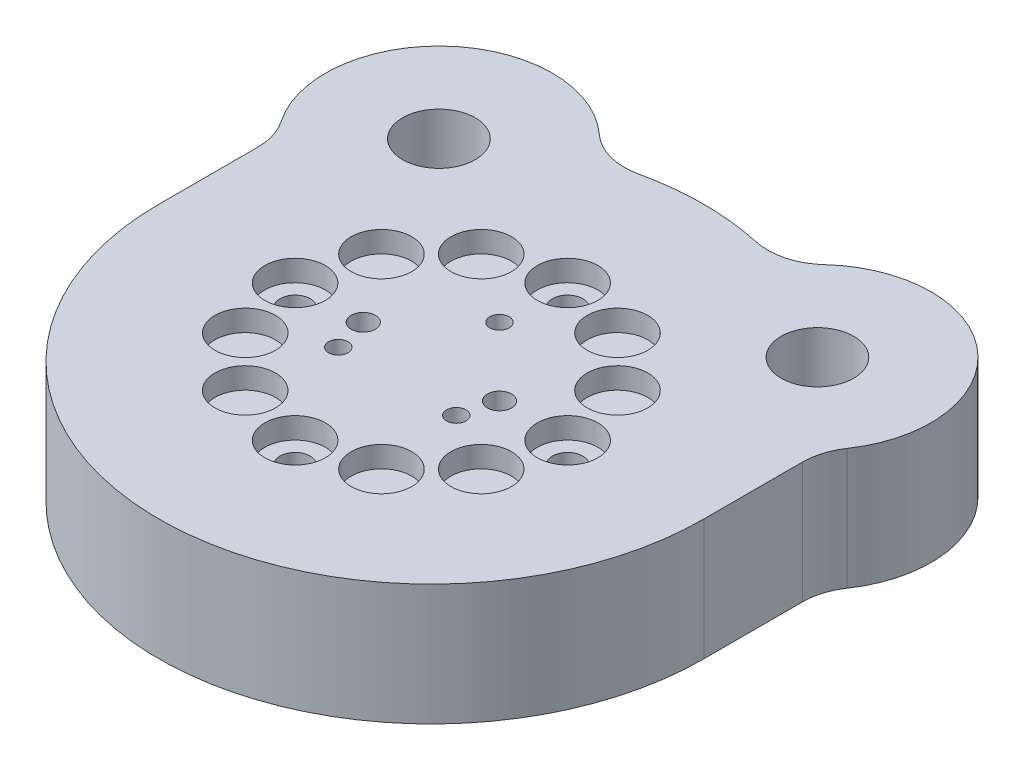
SolidWorks part; units mm, degrees
material "Plain Carbon Steel"
ref_plane "Front Plane" through (0, 0, 0) normal (0, 0, 1) x (1, 0, 0)
ref_plane "Top Plane" through (0, 0, 0) normal (0, 1, 0) x (1, 0, 0)
ref_plane "Right Plane" through (0, 0, 0) normal (1, 0, 0) x (0, 0, -1)
other "Configuration Table"
sketch "Sketch1" plane through (0, 0, 0) normal (0, 1, 0) x (1, 0, 0)
  line L0 (-100, 0) -> (100, 0) construction
  line L1 (0, -100) -> (0, 100) construction
  line L2 (-90, 0) -> (-90, 39.5049)
  line L3 (90, 0) -> (90, 39.5049)
  arc A0 (-90, 0) -> (90, 0) centre (0, 0) ccw
  arc A1 (-30.5618, 84.6521) -> (-90, 39.5049) centre (-62.5, 65) ccw
  arc A2 (90, 39.5049) -> (30.5618, 84.6521) centre (62.5, 65) ccw
  arc A3 (-30.5618, 84.6521) -> (-83.389, 33.8568) centre (0, 0) ccw construction
  arc A4 (-83.389, 33.8568) -> (-30.5618, 84.6521) centre (-62.5, 65) ccw construction
  arc A5 (30.5618, 84.6521) -> (-30.5618, 84.6521) centre (0, 0) ccw
  arc A6 (83.389, 33.8568) -> (30.5618, 84.6521) centre (0, 0) ccw construction
  arc A7 (30.5618, 84.6521) -> (83.389, 33.8568) centre (62.5, 65) ccw construction
  arc A8 (-83.389, 33.8568) -> (-90, 0) centre (0, 0) ccw construction
  arc A9 (90, 0) -> (83.389, 33.8568) centre (0, 0) ccw construction
  arc A10 (-90, 39.5049) -> (-83.389, 33.8568) centre (-62.5, 65) ccw construction
  arc A11 (83.389, 33.8568) -> (90, 39.5049) centre (62.5, 65) ccw construction
  dimension "D3" = 180
  dimension "D4" = 75
  dimension "D1" = 200
  dimension "D2" = 200
  dimension "D5" = 65
  dimension "D6" = 125
extrude "Boss-Extrude1" add sketch "Sketch1" against normal blind 40
sketch "Sketch2" plane through (0, 0, 0) normal (0, 1, 0) x (1, 0, 0)
  line L0 (-81.25, 32.524) -> (-59.2695, 19.8336)
  line L1 (-90, 39.5049) -> (-90, 0) construction
  line L2 (-90, 39.5049) -> (-90, 0)
  line L3 (0, -62.5) -> (0, 62.5) construction
  line L4 (81.25, 32.524) -> (59.2695, 19.8336)
  line L5 (90, 0) -> (90, 39.5049) construction
  line L6 (90, 0) -> (90, 39.5049)
  arc A0 (-59.2695, 19.8336) -> (59.2695, 19.8336) centre (0, 0) ccw
  arc A1 (-30.5618, 84.6521) -> (-90, 39.5049) centre (-62.5, 65) ccw construction
  arc A2 (-90, 39.5049) -> (-81.25, 32.524) centre (-62.5, 65) ccw
  arc A3 (-81.25, 32.524) -> (-69.2916, 28.1201) centre (-62.5, 65) ccw construction
  arc A4 (-30.5618, 84.6521) -> (-90, 39.5049) centre (-62.5, 65) ccw construction
  arc A5 (-90, 0) -> (90, 0) centre (0, 0) ccw construction
  arc A6 (-90, 0) -> (90, 0) centre (0, 0) ccw
  arc A7 (90, 39.5049) -> (81.25, 32.524) centre (62.5, 65) cw
  arc A8 (0, 62.5) -> (-59.2695, 19.8336) centre (0, 0) ccw construction
  arc A9 (59.2695, 19.8336) -> (0, 62.5) centre (0, 0) ccw construction
  dimension "D1" = 125
  dimension "D2" = 60
fillet "Fillet1" radius 20 4 edges at (30.5618, -20, -84.6521) (-30.5618, -20, -84.6521) (90, -20, -39.5049) (-90, -20, -39.5049)
sketch "Sketch3" plane through (0, 0, 0) normal (0, 1, 0) x (1, 0, 0)
  circle A0 centre (-62.5, 65) radius 12
  circle A1 centre (62.5, 65) radius 12
  dimension "D1" = 24
extrude "Cut-Extrude2" cut sketch "Sketch3" against normal up to next
sketch "Sketch4" plane through (0, 0, 0) normal (0, 1, 0) x (1, 0, 0)
  circle A0 centre (0, 0) radius 45 construction
  circle A1 centre (0, 45) radius 10
  dimension "D1" = 90
  dimension "D2" = 20
extrude "Cut-Extrude3" cut sketch "Sketch4" against normal blind 7
pattern_circular "CirPattern1" count 12 every 30 about axis through (0, 0, 0) along (0, 1, 0) of "Cut-Extrude3"
hole_wizard "Ø10.0 (10) Diameter Hole1" positions "Sketch7" profile "Sketch6" hole size "Ø10.0" standard "ISO" end condition through all
sketch "Sketch7" plane through (0, 0, 0) normal (0, 1, 0) x (1, 0, 0)
  point P0 (0, 45)
  point P3 (45, 0)
  point P6 (0, -45)
  point P9 (-45, 0)
sketch "Sketch6" plane through (0, 0, -45) normal (1, 0, 0) x (0, 0, 1)
  line L0 (0, 0) -> (0, 40)
  line L1 (0, 40) -> (5, 40)
  line L2 (5, 40) -> (5, 0)
  line L5 (5, 0) -> (0, 0)
  line L11 (0, -6.35) -> (0, 107.95) construction
  dimension "Thru Hole Dia." = 10
  dimension "Thru Hole Depth" = 40
sketch "Sketch8" plane through (0, -40, 0) normal (0, -1, 0) x (1, 0, 0)
  circle A0 centre (0, 45) radius 8.5
  circle A1 centre (45, 0) radius 8.5
  circle A2 centre (0, -45) radius 8.5
  circle A3 centre (-45, 0) radius 8.5
  dimension "D1" = 17
extrude "Cut-Extrude4" cut sketch "Sketch8" against normal blind 23
hole_wizard "CBORE for M6 Hex Socket Head Cap Screw1" positions "Sketch14" profile "Sketch13" counterbore size "M6" standard "ISO" end condition through all
sketch "Sketch14" plane through (0, -40, 0) normal (0, -1, 0) x (-1, 0, 0)
  point P0 (0, 22.5)
  point P3 (-19.4856, -11.25)
  point P6 (19.4856, -11.25)
sketch "Sketch13" plane through (0, -40, -22.5) normal (1, 0, 0) x (0, 0, -1)
  line L0 (0, 0) -> (0, 40)
  line L1 (0, 40) -> (3.2, 40)
  line L3 (3.2, 40) -> (3.2, 6.4)
  line L4 (3.2, 6.4) -> (5.5, 6.4)
  line L5 (5.5, 6.4) -> (5.5, 0)
  line L7 (5.5, 0) -> (0, 0)
  line L11 (0, -6.35) -> (0, 107.95) construction
  dimension "Thru Hole Dia." = 6.4
  dimension "Thru Hole Depth" = 40
  dimension "C'Bore Dia." = 11
  dimension "C'Bore Depth" = 6.4
hole_wizard "Ø8.0mm Dowel Hole1" positions "Sketch17" profile "Sketch16" hole size "Ø8.0" standard "ISO" end condition through all
sketch "Sketch17" plane through (0, 0, 0) normal (0, 1, 0) x (1, 0, 0)
  point P0 (-22.5, 0)
  point P3 (22.5, 0)
sketch "Sketch16" plane through (-22.5, 0, 0) normal (1, 0, 0) x (0, 0, 1)
  line L0 (0, 0) -> (0, 40)
  line L1 (0, 40) -> (4, 40)
  line L2 (4, 40) -> (4, 0)
  line L5 (4, 0) -> (0, 0)
  line L11 (0, -6.35) -> (0, 107.95) construction
  dimension "Thru Hole Dia." = 8
  dimension "Thru Hole Depth" = 40
